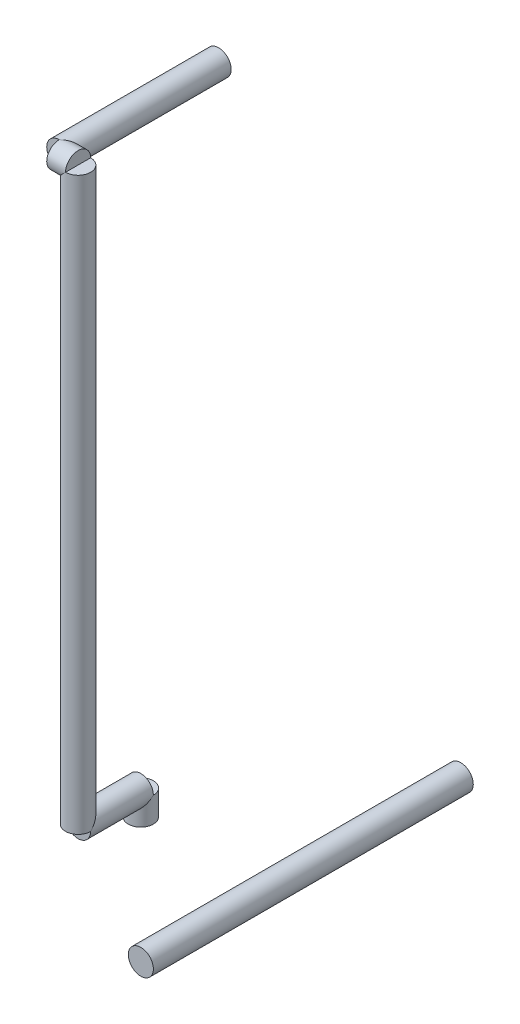
SolidWorks part; units mm, degrees
ref_plane "Front Plane" through (0, 0, 0) normal (0, 0, 1) x (1, 0, 0)
ref_plane "Top Plane" through (0, 0, 0) normal (0, 1, 0) x (1, 0, 0)
ref_plane "Right Plane" through (0, 0, 0) normal (1, 0, 0) x (0, 0, -1)
ref_plane "Plane1" through (0, -94.5, 0) normal (0, 1, 0) x (1, 0, 0)
sketch "Sketch1" plane through (0, -94.5, 0) normal (0, 1, 0) x (1, 0, 0)
  circle A0 centre (32, -26) radius 2
ref_plane "Plane2" through (0, 0, -25) normal (0, 0, 1) x (1, 0, 0)
sketch "Sketch2" plane through (0, 0, -25) normal (0, 0, 1) x (1, 0, 0)
  circle A0 centre (32, -94.5) radius 2
extrude "Boss-Extrude1" add sketch "Sketch2" along normal blind 51
ref_plane "Plane3" through (0, -74.5, 0) normal (0, 1, 0) x (1, 0, 0)
sketch "Sketch3" plane through (0, -74.5, 0) normal (0, 1, 0) x (1, 0, 0)
  circle A0 centre (32, -26) radius 2
extrude "Boss-Extrude2" add sketch "Sketch3" along normal blind 4
ref_plane "Plane4" through (0, 0, 26) normal (0, 0, 1) x (1, 0, 0)
sketch "Sketch4" plane through (0, 0, 26) normal (0, 0, 1) x (1, 0, 0)
  circle A0 centre (32, -70.5) radius 2
extrude "Boss-Extrude3" add sketch "Sketch4" along normal blind 10
ref_plane "Plane5" through (0, -70.5, 0) normal (0, 1, 0) x (1, 0, 0)
sketch "Sketch5" plane through (0, -70.5, 0) normal (0, 1, 0) x (1, 0, 0)
  circle A0 centre (32, -36) radius 2
extrude "Boss-Extrude4" add sketch "Sketch5" along normal blind 91
ref_plane "Plane6" through (29, 0, 0) normal (1, 0, 0) x (0, 0, -1)
sketch "Sketch6" plane through (29, 0, 0) normal (1, 0, 0) x (0, 0, -1)
  circle A0 centre (-36, 20.5) radius 2
extrude "Boss-Extrude5" add sketch "Sketch6" along normal blind 3
ref_plane "Plane7" through (0, 0, 10.6) normal (0, 0, 1) x (1, 0, 0)
sketch "Sketch7" plane through (0, 0, 10.6) normal (0, 0, 1) x (1, 0, 0)
  circle A0 centre (29, 20.5) radius 2
extrude "Boss-Extrude6" add sketch "Sketch7" along normal blind 25.4
